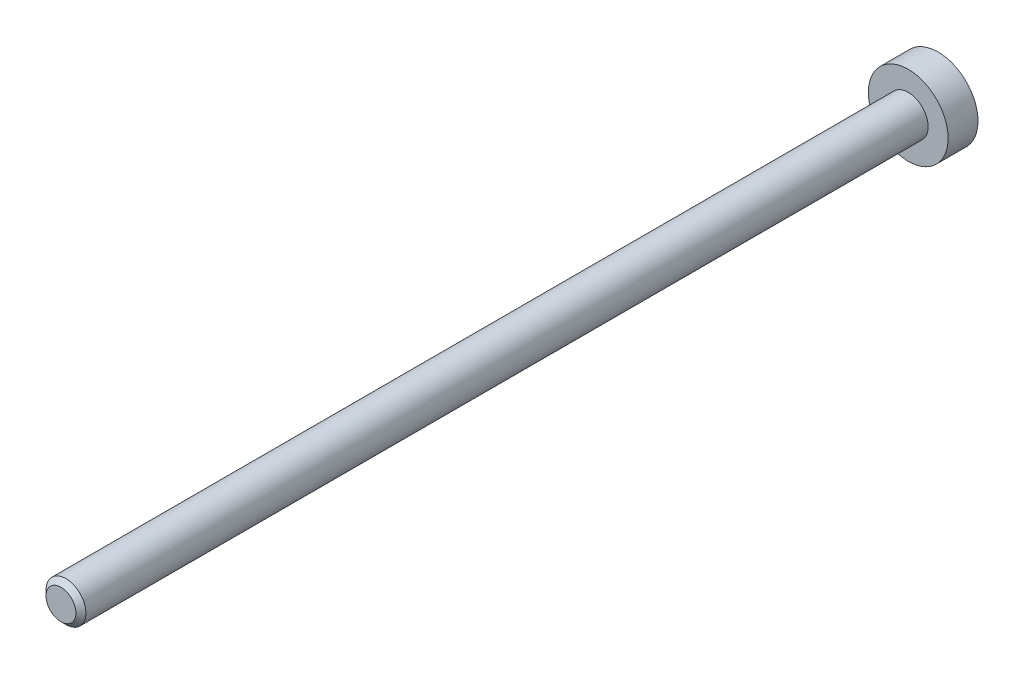
SolidWorks part; units mm, degrees
ref_plane "Front Plane" through (0, 0, 0) normal (0, 0, 1) x (1, 0, 0)
ref_plane "Top Plane" through (0, 0, 0) normal (0, 1, 0) x (1, 0, 0)
ref_plane "Right Plane" through (0, 0, 0) normal (1, 0, 0) x (0, 0, -1)
sketch "Sketch1" plane through (0, 0, 0) normal (0, 0, 1) x (1, 0, 0)
  circle A0 centre (0, 0) radius 4
  dimension "D1" = 8
extrude "Boss-Extrude1" add sketch "Sketch1" along normal blind 3
sketch "Sketch2" plane through (0, 0, 3) normal (0, 0, 1) x (1, 0, 0)
  circle A0 centre (0, 0) radius 2
  dimension "D1" = 4
extrude "Boss-Extrude2" add sketch "Sketch2" along normal blind 85
chamfer "Chamfer2" distance 0.5 angle 45 1 edges at (2, 0, 88)
